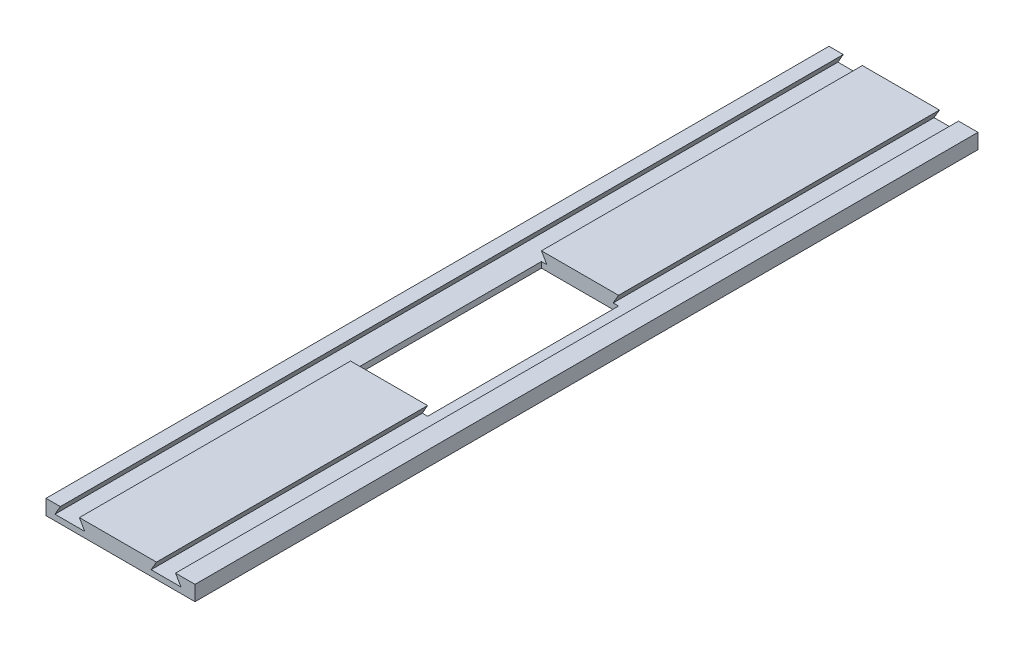
SolidWorks part; units mm, degrees
ref_plane "Front Plane" through (0, 0, 0) normal (0, 0, 1) x (1, 0, 0)
ref_plane "Top Plane" through (0, 0, 0) normal (0, 1, 0) x (1, 0, 0)
ref_plane "Right Plane" through (0, 0, 0) normal (1, 0, 0) x (0, 0, -1)
sketch "Sketch1" plane through (0, 0, 0) normal (0, 0, 1) x (1, 0, 0)
  line L2 (-1237.1862, 885.422) -> (-1224.0522, 885.422) construction
  line L4 (-1242.6862, 885.422) -> (-1240.2862, 885.422)
  line L5 (-1242.6862, 885.422) -> (-1240.1862, 885.422) construction
  line L6 (-1240.2862, 885.422) -> (-1241.1862, 883.8632)
  line L7 (-1241.1862, 883.8632) -> (-1236.1862, 883.8632)
  line L8 (-1236.1862, 883.8632) -> (-1237.0862, 885.422)
  line L9 (-1237.0862, 885.422) -> (-1224.1522, 885.422)
  line L10 (-1242.6862, 885.422) -> (-1242.6862, 882.8935)
  line L13 (-1236.3202, 883.922) -> (-1237.1862, 885.422) construction
  line L14 (-1240.1862, 885.422) -> (-1241.0522, 883.922) construction
  line L18 (-1220.9522, 885.422) -> (-1220.0522, 883.8632)
  line L19 (-1220.0522, 883.8632) -> (-1225.0522, 883.8632)
  line L20 (-1225.0522, 883.8632) -> (-1224.1522, 885.422)
  line L24 (-1220.9522, 885.422) -> (-1217.6862, 885.422)
  line L25 (-1217.6862, 885.422) -> (-1217.6862, 882.8935)
  line L26 (-1242.6862, 882.8935) -> (-1217.6862, 882.8935)
  dimension "D1" = 5
  dimension "D2" = 0.1
  dimension "D3" = 0.1
  dimension "D4" = 0.1
  dimension "D5" = 882.8935
extrude "Boss-Extrude1" add sketch "Sketch1" along normal blind 150
sketch "Sketch5" plane through (0, 885.422, 0) normal (0, 1, 0) x (1, 0, 0)
  line L0 (-1237.0862, -53.8357) -> (-1224.1522, -53.8357)
  line L1 (-1237.0862, -150) -> (-1237.0862, 0) construction
  line L2 (-1224.1522, -150) -> (-1224.1522, 0) construction
  line L3 (-1224.1522, -53.8357) -> (-1224.1522, -85.8685)
  line L4 (-1224.1522, -85.8685) -> (-1237.0862, -85.8685)
  line L5 (-1237.0862, -85.8685) -> (-1237.0862, -53.8357)
  line L6 (-1224.1522, 0) -> (-1237.0862, 0) construction
  dimension "D1" = 53.8357
  dimension "D2" = 85.8685
extrude "Cut-Extrude4" cut sketch "Sketch5" against normal up to surface (2.5285 mm away) up to face at (-1230.1862, 882.8935, 75)
sketch "Sketch7" plane through (0, 882.8935, 0) normal (0, -1, 0) x (-1, 0, 0)
  line L0 (1217.6862, -150) -> (1217.6862, 0) construction
  line L1 (1242.6862, -150) -> (1217.6862, -150)
  line L2 (1242.6862, -150) -> (1242.6862, -131.36)
  line L3 (1242.6862, -131.36) -> (1217.6862, -131.36)
  line L4 (1217.6862, -150) -> (1217.6862, -131.36)
  dimension "D1" = 18.64
extrude "Cut-Extrude5" cut sketch "Sketch7" against normal through all
